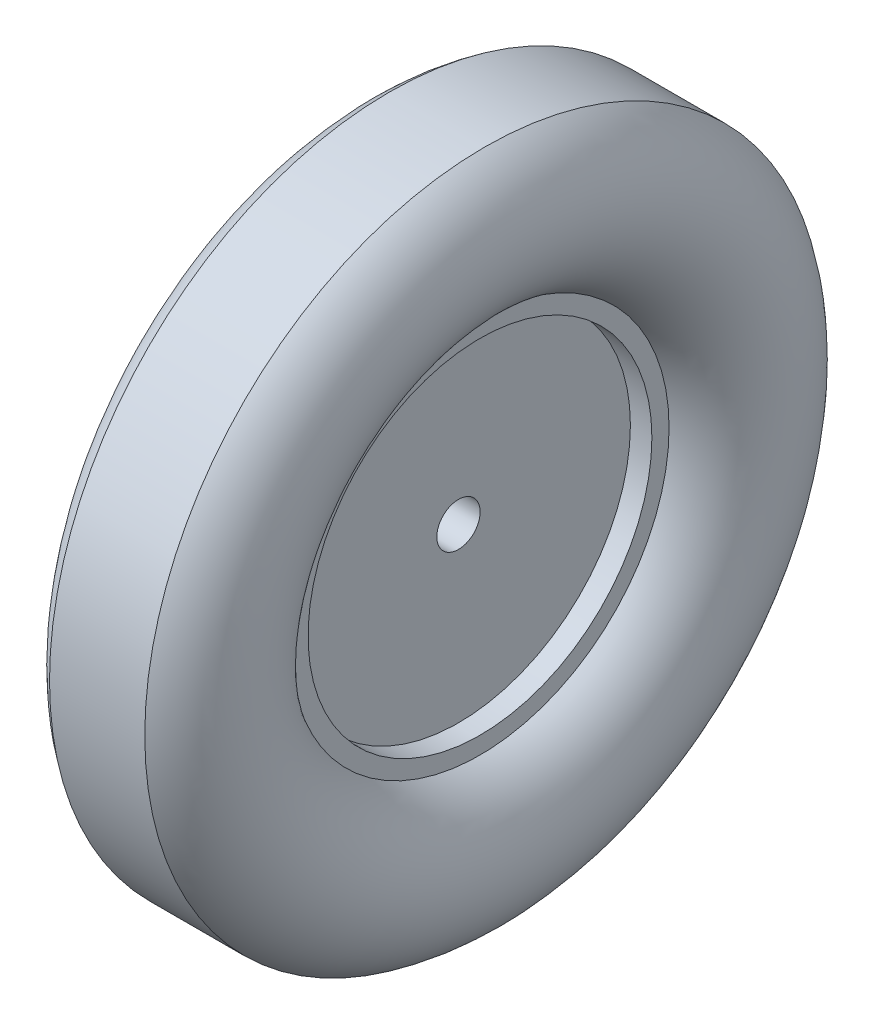
SolidWorks part; units mm, degrees
ref_plane "Front Plane" through (0, 0, 0) normal (0, 0, 1) x (1, 0, 0)
ref_plane "Top Plane" through (0, 0, 0) normal (0, 1, 0) x (1, 0, 0)
ref_plane "Right Plane" through (0, 0, 0) normal (1, 0, 0) x (0, 0, -1)
sketch "Sketch1" plane through (0, 0, 0) normal (0, 0, 1) x (1, 0, 0)
  line L0 (12.7, 0) -> (-12.7, 0)
  line L1 (-12.7, 0) -> (-12.7, 101.6)
  line L2 (12.7, 0) -> (12.7, 101.6)
  line L3 (12.7, 101.6) -> (25.3994, 101.6)
  line L4 (25.3994, 101.6) -> (25.3994, 111.76)
  line L5 (25.3994, 111.76) -> (-25.4006, 111.76)
  line L6 (-25.4006, 111.76) -> (-25.4006, 101.6)
  line L7 (-25.4006, 101.6) -> (-12.7, 101.6)
  line L8 (-0.0006, 157.1385) -> (-0.0006, 209.1421)
  line L9 (28.1513, 200.8631) -> (-28.1525, 200.8631)
  line L10 (0, 0) -> (0, 12.805)
  line L11 (0, 12.805) -> (-12.7, 12.805)
  line L12 (0, 12.805) -> (12.7, 12.805)
  arc A0 (-25.4006, 111.76) -> (25.3994, 111.76) centre (-0.0006, 157.1385) cw
  point P4 (0, 0)
  point P15 (-0.0006, 278.0624)
  point P20 (-0.0006, 200.8631)
  dimension "D1" = 25.4
  dimension "D2" = 101.6
  dimension "D3" = 101.6
  dimension "D4" = 50.8
  dimension "D5" = 10.16
  dimension "D6" = 10.16
revolve "Revolve1" add sketch "Sketch1" angle 360 about L0
scale "Scale1" scale about centroid uniform scaling yes scale factor 1.5
